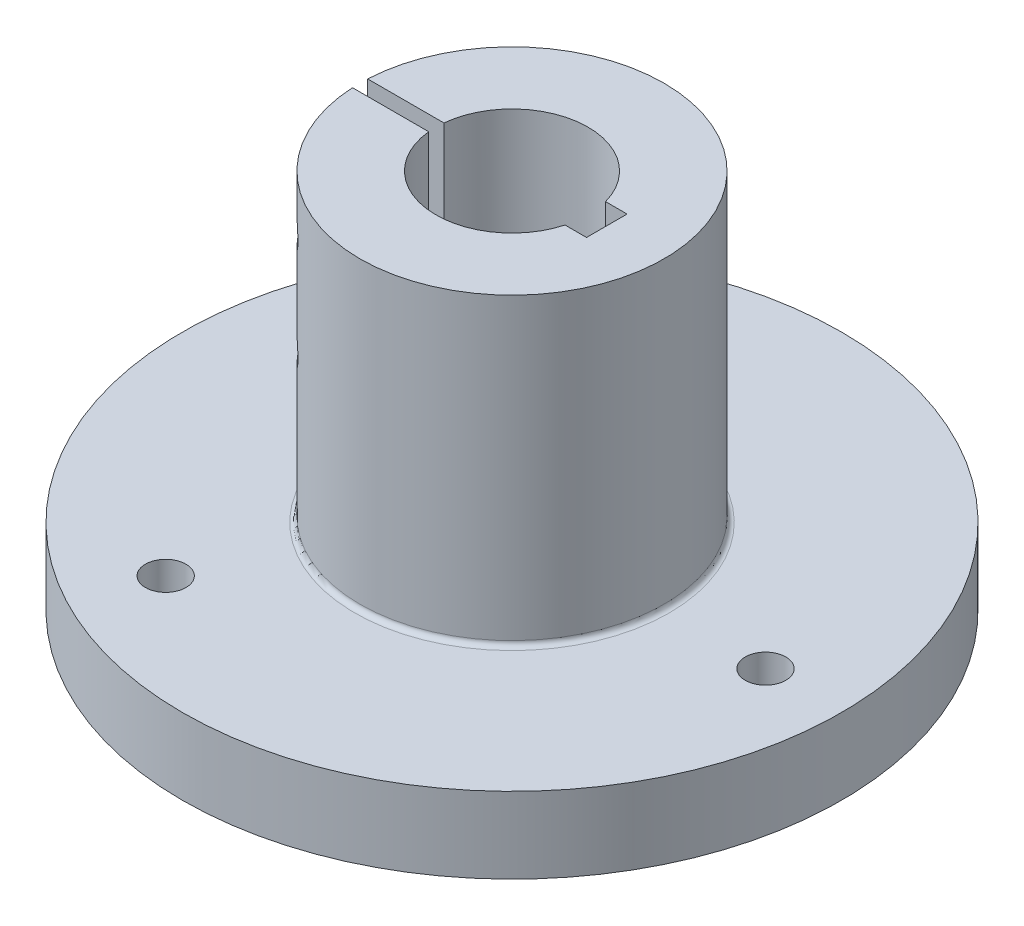
SolidWorks part; units mm, degrees
material "6061 Alloy"
ref_plane "Front Plane" through (0, 0, 0) normal (0, 0, 1) x (1, 0, 0)
ref_plane "Top Plane" through (0, 0, 0) normal (0, 1, 0) x (1, 0, 0)
ref_plane "Right Plane" through (0, 0, 0) normal (1, 0, 0) x (0, 0, -1)
sketch "Sketch2" plane through (0, 0, 0) normal (0, 1, 0) x (1, 0, 0)
  line L0 (0, 0) -> (50, 0) construction
  line L1 (0, 0) -> (-131.5364, 0) construction
  line L3 (11.3, 4) -> (18.7, 4)
  line L4 (11.3, 4) -> (11.3, -4)
  line L5 (11.3, -4) -> (18.7, -4)
  line L6 (18.7, 4) -> (18.7, -4)
  line L7 (11.3, 4) -> (18.7, -4) construction
  line L8 (11.3, -4) -> (18.7, 4) construction
  arc A0 (-32.5, -56.2917) -> (-32.5, 56.2917) centre (0, 0) ccw construction
  circle A1 centre (0, 0) radius 15 construction
  circle A5 centre (50, 0) radius 4 construction
  circle A6 centre (-25, -43.3013) radius 4 construction
  circle A7 centre (-25, 43.3013) radius 4 construction
  arc A8 (52.0567, -14.8583) -> (52.0567, 14.8583) centre (50, 0) ccw
  arc A9 (-13.1607, 52.5116) -> (-38.896, 37.6533) centre (-25, 43.3013) ccw
  arc A10 (-38.896, -37.6533) -> (-13.1607, -52.5116) centre (-25, -43.3013) ccw
  arc A11 (-38.896, -37.6533) -> (-38.896, 37.6533) centre (-131.5364, 0) ccw
  arc A12 (-13.1607, 52.5116) -> (52.0567, 14.8583) centre (65.7682, 113.9138) ccw
  arc A13 (52.0567, -14.8583) -> (-13.1607, -52.5116) centre (65.7682, -113.9138) ccw
  circle A14 centre (-25, 43.3013) radius 3.4
  circle A15 centre (50, 0) radius 3.4
  circle A16 centre (-25, -43.3013) radius 3.4
  point P6 (15, 0)
  point P12 (-0.395, 0.2281)
  point P13 (0, 0)
  point P28 (0, 0)
  dimension "D1" = 130
  dimension "D2" = 30
  dimension "D4" = 8
  dimension "D5" = 200
  dimension "D9" = 6.8
  dimension "D3" = 50
  dimension "D6" = 8
  dimension "D7" = 7.4
  dimension "D8" = 3
sketch "Sketch3" plane through (0, 0, 0) normal (0, 1, 0) x (1, 0, 0)
  line L4 (18.7, 4) -> (11.3, 4)
  line L5 (11.3, 4) -> (11.3, -4)
  line L6 (11.3, -4) -> (18.7, -4)
  line L7 (18.7, -4) -> (18.7, 4)
  line L8 (18.7, 4) -> (14.4568, 4)
  line L10 (14.4568, -4) -> (18.7, -4)
  line L11 (18.7, -4) -> (18.7, 4)
  circle A0 centre (0, 0) radius 15 construction
  circle A1 centre (-25, 43.3013) radius 4
  circle A2 centre (-25, 43.3013) radius 4
  circle A3 centre (-25, -43.3013) radius 4
  circle A4 centre (-25, -43.3013) radius 4
  circle A5 centre (50, 0) radius 4
  circle A6 centre (50, 0) radius 4
  arc A7 (14.4568, 4) -> (14.4568, -4) centre (0, 0) ccw
  arc A12 (52.0567, -14.8583) -> (52.0567, 14.8583) centre (50, 0) ccw
  arc A13 (-13.1607, 52.5116) -> (52.0567, 14.8583) centre (65.7682, 113.9138) ccw
  arc A14 (-13.1607, 52.5116) -> (-38.896, 37.6533) centre (-25, 43.3013) ccw
  arc A15 (-38.896, -37.6533) -> (-38.896, 37.6533) centre (-131.5364, 0) ccw
  arc A16 (-38.896, -37.6533) -> (-13.1607, -52.5116) centre (-25, -43.3013) ccw
  arc A17 (52.0567, -14.8583) -> (-13.1607, -52.5116) centre (65.7682, -113.9138) ccw
  arc A18 (52.0567, -14.8583) -> (52.0567, 14.8583) centre (50, 0) ccw
  arc A19 (-13.1607, 52.5116) -> (52.0567, 14.8583) centre (65.7682, 113.9138) ccw
  arc A20 (-13.1607, 52.5116) -> (-38.896, 37.6533) centre (-25, 43.3013) ccw
  arc A21 (-38.896, -37.6533) -> (-38.896, 37.6533) centre (-131.5364, 0) ccw
  arc A22 (-38.896, -37.6533) -> (-13.1607, -52.5116) centre (-25, -43.3013) ccw
  arc A23 (52.0567, -14.8583) -> (-13.1607, -52.5116) centre (65.7682, -113.9138) ccw
  dimension "D1" = 0
  dimension "D2" = 0
  dimension "D3" = 0
  dimension "D4" = 0
  dimension "D5" = 0
extrude "Boss-Extrude1" add sketch "Sketch3" along normal blind 15
sketch "Sketch4" plane through (0, 15, 0) normal (0, 1, 0) x (1, 0, 0)
  line L0 (14.4568, -4) -> (18.7, -4) construction
  line L1 (18.7, -4) -> (18.7, 4) construction
  line L2 (18.7, 4) -> (14.4568, 4) construction
  line L3 (14.4568, -4) -> (18.7, -4)
  line L4 (18.7, -4) -> (18.7, 4)
  line L5 (18.7, 4) -> (14.4568, 4)
  line L6 (-15, 0) -> (-30, 0) construction
  line L8 (-31.5, 1.5) -> (-13.5, 1.5)
  line L9 (-31.5, 1.5) -> (-31.5, -1.5)
  line L10 (-31.5, -1.5) -> (-13.5, -1.5)
  line L11 (-13.5, 1.5) -> (-13.5, -1.5)
  line L12 (-31.5, 1.5) -> (-13.5, -1.5) construction
  line L13 (-31.5, -1.5) -> (-13.5, 1.5) construction
  circle A0 centre (0, 0) radius 30
  arc A1 (14.4568, 4) -> (14.4568, -4) centre (0, 0) ccw construction
  arc A2 (14.4568, 4) -> (14.4568, -4) centre (0, 0) ccw
  point P9 (-22.5, 0)
  line M10 (14.4568, 4) -> (18.7, 4)
  line M11 (18.7, 4) -> (18.7, -4)
  line M12 (18.7, -4) -> (14.4568, -4)
  arc M13 (14.4568, -4) -> (14.4568, 4) centre (0, 0) cw
  dimension "D1" = 60
  dimension "D2" = 3
  dimension "D3" = 18
extrude "Boss-Extrude2" add sketch "Sketch4" along normal blind 60 contours L10 A0 L8 M13 M10 M11 M12
fillet "Fillet1" radius 1 1 edges at (30, 15, 0)
sketch "Sketch6" plane through (0, 0, 0) normal (0, 0, 1) x (1, 0, 0)
  line L0 (-29.9625, 75) -> (-14.9248, 75) construction
  line L1 (-29.9625, 75) -> (-14.9248, 75) construction
  line L2 (-22.4436, 75) -> (-22.4436, 65) construction
  line L3 (-22.4436, 65) -> (-22.4436, 45) construction
  circle A0 centre (-22.4436, 65) radius 3.4
  circle A1 centre (-22.4436, 45) radius 3.4
  dimension "D3" = 6.8
  dimension "D1" = 10
  dimension "D2" = 20
extrude "Cut-Extrude1" cut sketch "Sketch6" along normal through all
sketch "Sketch7" plane through (0, 0, 0) normal (0, 0, 1) x (1, 0, 0)
  circle A0 centre (-22.4436, 65) radius 4
  circle A1 centre (-22.4436, 45) radius 3.4
  circle A2 centre (-22.4436, 45) radius 3.4 construction
  circle A3 centre (-22.4436, 65) radius 3.4
  circle A4 centre (-22.4436, 65) radius 3.4 construction
  circle A5 centre (-22.4436, 45) radius 4
  dimension "D3" = 8
  dimension "D1" = 0
  dimension "D2" = 0
extrude "Cut-Extrude2" cut sketch "Sketch7" against normal through all
sketch "Sketch8" plane through (0, 0, 0) normal (0, 0, 1) x (1, 0, 0)
  circle A0 centre (-22.4436, 45) radius 4 construction
  circle A1 centre (-22.4436, 65) radius 4 construction
  circle A2 centre (-22.4436, 45) radius 4 construction
  circle A3 centre (-22.4436, 65) radius 4 construction
  circle A4 centre (-22.4436, 65) radius 7
  circle A5 centre (-22.4436, 45) radius 7
  dimension "D1" = 14
extrude "Cut-Extrude3" cut sketch "Sketch8" against normal through all from offset 6 offset against normal yes
sketch "Sketch9" plane through (0, 0, 0) normal (0, 1, 0) x (1, 0, 0)
  circle A0 centre (0, 0) radius 65
  arc A1 (-38.896, -37.6533) -> (-13.1607, -52.5116) centre (-25, -43.3013) ccw construction
  arc A2 (52.0567, -14.8583) -> (-13.1607, -52.5116) centre (65.7682, -113.9138) ccw construction
  arc A3 (52.0567, -14.8583) -> (52.0567, 14.8583) centre (50, 0) ccw construction
  arc A4 (-13.1607, 52.5116) -> (52.0567, 14.8583) centre (65.7682, 113.9138) ccw construction
  arc A5 (-13.1607, 52.5116) -> (-38.896, 37.6533) centre (-25, 43.3013) ccw construction
  arc A6 (-38.896, -37.6533) -> (-38.896, 37.6533) centre (-131.5364, 0) ccw construction
  arc A7 (-38.896, -37.6533) -> (-13.1607, -52.5116) centre (-25, -43.3013) ccw
  arc A8 (52.0567, -14.8583) -> (-13.1607, -52.5116) centre (65.7682, -113.9138) ccw
  arc A9 (52.0567, -14.8583) -> (52.0567, 14.8583) centre (50, 0) ccw
  arc A10 (-13.1607, 52.5116) -> (52.0567, 14.8583) centre (65.7682, 113.9138) ccw
  arc A11 (-13.1607, 52.5116) -> (-38.896, 37.6533) centre (-25, 43.3013) ccw
  arc A12 (-38.896, -37.6533) -> (-38.896, 37.6533) centre (-131.5364, 0) ccw
  dimension "D1" = 130
extrude "Boss-Extrude3" add sketch "Sketch9" along normal up to surface (15 mm away) contours A7 A12 A11 A0 | A11 A10 A9 A0 | A9 A8 A7 A0 up to face at (-25, 15, 47.3013)
thread "Thread1" pitch 1.25 start angle 0, offset 1, length 25, pitch 1.25, diameter 6.8
ref_plane "Plane1" through (-19.0436, 60, 0.5) normal (0, -1, 0) x (1, 0, 0)
sketch "Thread Profile1" plane through (-19.0436, 60, 0.5) normal (0, -1, 0) x (1, 0, 0)
  line L0 (0, 0) -> (0, 1.25) construction
  line L1 (0, 0) -> (0.6766, 0.3906)
  line L2 (0.6766, 0.3906) -> (0.6766, 0.5469)
  line L3 (0.6766, 0.5469) -> (0, 0.9375)
  line L4 (0.6766, 0.4687) -> (0, 0.4687) construction
  line L11 (0, 0) -> (0, 0.9375)
  point P2 (0, 0)
  dimension "Pitch" = 1.25
  dimension "Profile_Angle" = 60
  dimension "Profile_Land" = 0.1562
  dimension "Profile_Height" = 0.6766
thread "Thread2" pitch 1.25 start angle 0, offset 1, length 25, pitch 1.25, diameter 6.8
ref_plane "Plane2" through (-19.0436, 40, 0.5) normal (0, -1, 0) x (1, 0, 0)
sketch "Thread Profile2" plane through (-19.0436, 40, 0.5) normal (0, -1, 0) x (1, 0, 0)
  line L0 (0, 0) -> (0, 1.25) construction
  line L1 (0, 0) -> (0.6766, 0.3906)
  line L2 (0.6766, 0.3906) -> (0.6766, 0.5469)
  line L3 (0.6766, 0.5469) -> (0, 0.9375)
  line L4 (0.6766, 0.4687) -> (0, 0.4687) construction
  line L11 (0, 0) -> (0, 0.9375)
  point P2 (0, 0)
  dimension "Pitch" = 1.25
  dimension "Profile_Angle" = 60
  dimension "Profile_Land" = 0.1562
  dimension "Profile_Height" = 0.6766
